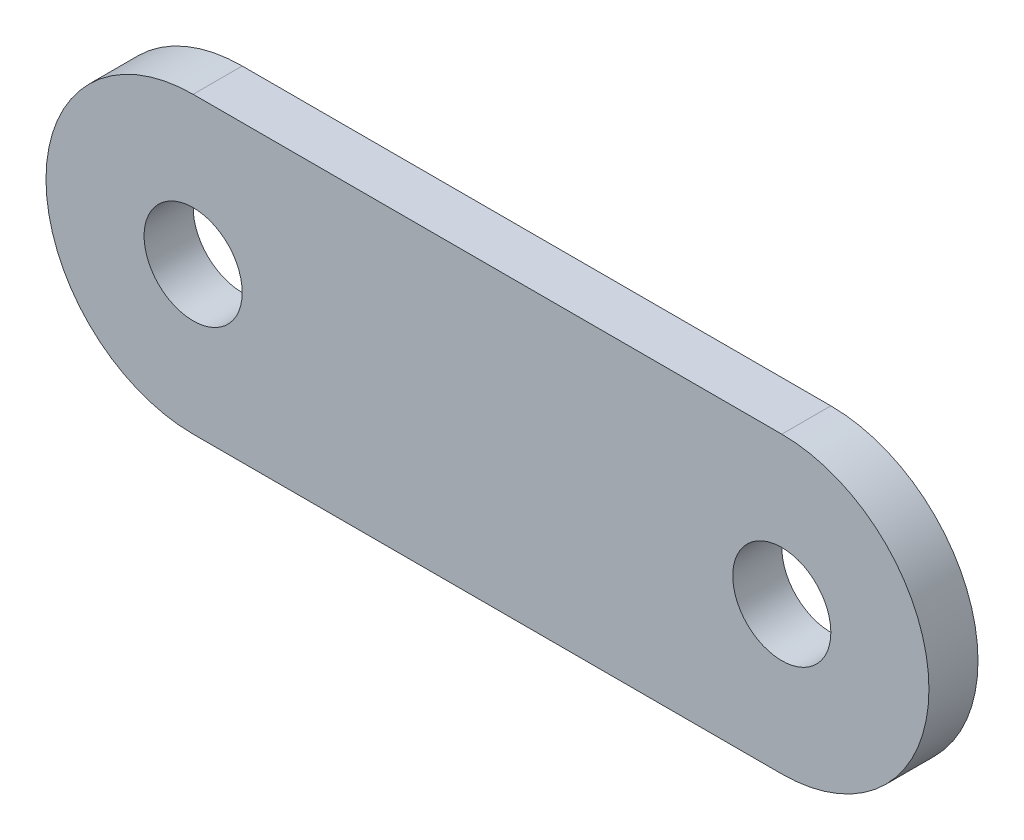
SolidWorks part; units mm, degrees
material "Fundición gris (SN)"
ref_plane "Alzado" through (0, 0, 0) normal (0, 0, 1) x (1, 0, 0)
ref_plane "Planta" through (0, 0, 0) normal (0, 1, 0) x (1, 0, 0)
ref_plane "Vista lateral" through (0, 0, 0) normal (1, 0, 0) x (0, 0, -1)
sketch "Croquis1" plane through (0, 0, 0) normal (0, 0, 1) x (1, 0, 0)
  line L0 (-6, 0) -> (6, 0) construction
  line L1 (-6, 3) -> (6, 3)
  line L2 (-6, -3) -> (6, -3)
  arc A0 (-6, 3) -> (-6, -3) centre (-6, 0) ccw
  arc A1 (6, -3) -> (6, 3) centre (6, 0) ccw
  circle A2 centre (6, 0) radius 1
  circle A3 centre (-6, 0) radius 1
  point P2 (0, 0)
  dimension "D2" = 3
  dimension "D3" = 2
  dimension "D4" = 2
  dimension "D1" = 12
extrude "Saliente-Extruir1" add sketch "Croquis1" along normal blind 1
